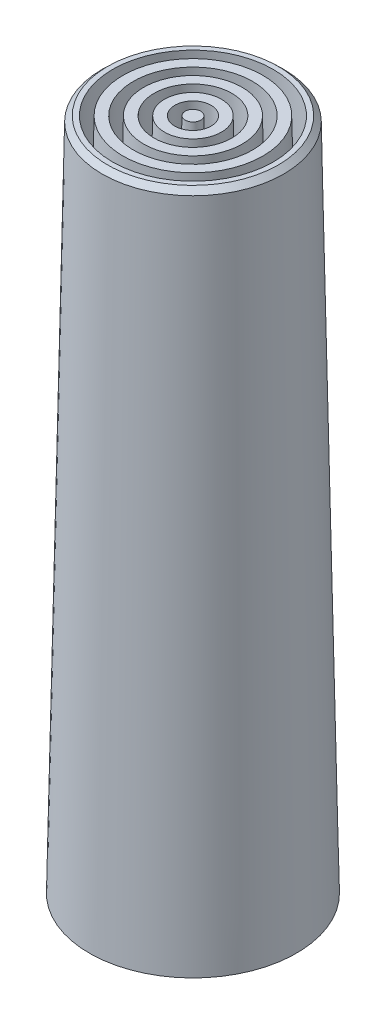
SolidWorks part; units mm, degrees
ref_plane "Front Plane" through (0, 0, 0) normal (0, 0, 1) x (1, 0, 0)
ref_plane "Top Plane" through (0, 0, 0) normal (0, 1, 0) x (1, 0, 0)
ref_plane "Right Plane" through (0, 0, 0) normal (1, 0, 0) x (0, 0, -1)
sketch "Sketch1" plane through (0, 0, 0) normal (0, 0, 1) x (1, 0, 0)
  line L0 (0, 0) -> (20, 0)
  line L1 (20, 0) -> (17.5, 130)
  line L2 (17.5, 130) -> (0, 130)
  line L3 (0, 130) -> (0, 0)
  dimension "D1" = 130
  dimension "D2" = 20
  dimension "D3" = 17.5
revolve "Revolve1" add sketch "Sketch1" angle 360 about L3
sketch "Sketch2" plane through (0, 0, 0) normal (0, 0, 1) x (1, 0, 0)
  line L0 (17.9996, 0) -> (15.5, 129.9808) construction
  line L1 (15.9993, 0) -> (13.4993, 130)
  line L2 (18.0004, -0.0385) -> (15.5004, 129.9615)
  line L3 (17.9996, 0) -> (15.4996, 130)
  line L4 (17.5, 130) -> (-17.5, 130) construction
  line L5 (16, -0.0385) -> (13.5004, 129.9423) construction
  line L6 (-20, 0) -> (20, 0) construction
  line L7 (15.9993, 0) -> (17.9996, 0)
  line L8 (13.4993, 130) -> (15.4996, 130)
  line L9 (0, 0) -> (0, 130) construction
  line L10 (13.9989, 0) -> (11.4989, 130)
  line L11 (11.9985, 0) -> (9.4985, 130)
  line L12 (9.9982, 0) -> (7.4982, 130)
  line L13 (7.9978, 0) -> (5.4978, 130)
  line L14 (5.9974, 0) -> (3.4974, 130)
  line L15 (3.997, 0) -> (1.497, 130)
  line L16 (13.9996, -0.0385) -> (11.4996, 129.9615) construction
  line L17 (12, -0.0769) -> (9.5, 129.9231) construction
  line L18 (10.0004, -0.1154) -> (7.5004, 129.8846) construction
  line L19 (8.0007, -0.1538) -> (5.5007, 129.8462) construction
  line L20 (6.0011, -0.1923) -> (3.5011, 129.8077) construction
  line L21 (4.0015, -0.2307) -> (1.5015, 129.7693) construction
  line L22 (11.4989, 130) -> (9.4985, 130)
  line L23 (7.4982, 130) -> (5.4978, 130)
  line L24 (3.4974, 130) -> (1.497, 130)
  line L25 (13.9989, 0) -> (11.9985, 0)
  line L26 (9.9982, 0) -> (7.9978, 0)
  line L27 (5.9974, 0) -> (3.997, 0)
  dimension "D1" = 2
  dimension "D2" = 2
  dimension "D3" = 2
  dimension "D4" = 2
  dimension "D5" = 2
  dimension "D6" = 2
  dimension "D7" = 2
  dimension "D8" = 2
revolve "Cut-Revolve1" cut sketch "Sketch2" angle 360 about L9
chamfer "Chamfer1" distance 1 angle 45 1 edges at (-17.5, 130, 0)
